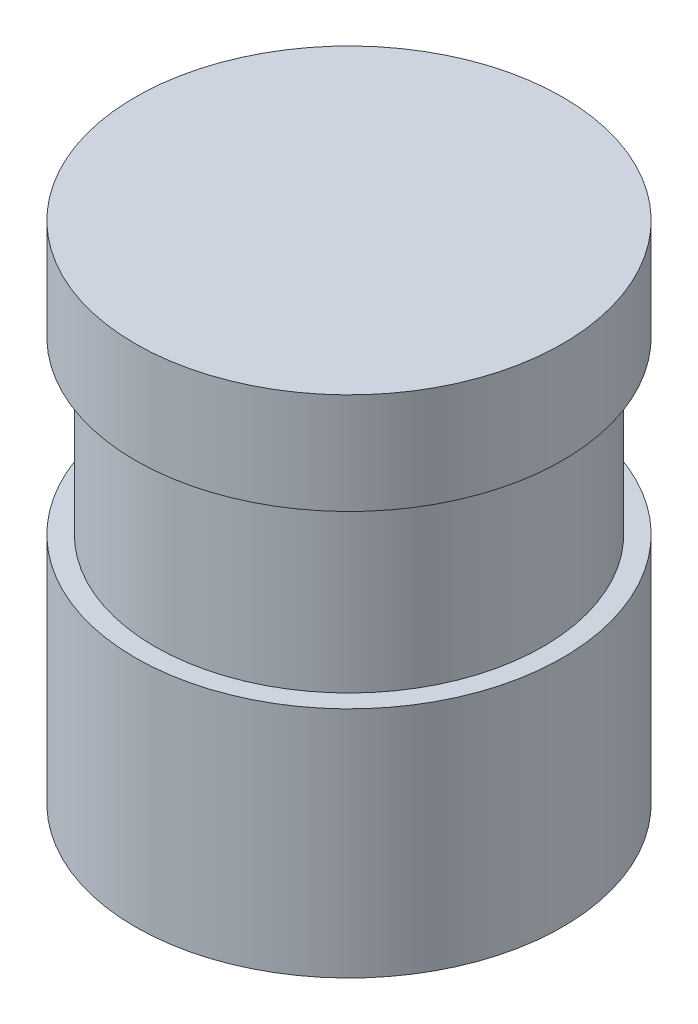
SolidWorks part; units mm, degrees
ref_plane "Спереди" through (0, 0, 0) normal (0, 0, 1) x (1, 0, 0)
ref_plane "Сверху" through (0, 0, 0) normal (0, 1, 0) x (1, 0, 0)
ref_plane "Справа" through (0, 0, 0) normal (1, 0, 0) x (0, 0, -1)
other "Configuration Table"
sketch "Эскиз1" plane through (0, 0, 0) normal (0, 1, 0) x (1, 0, 0)
  circle A0 centre (0, 0) radius 27.5
  dimension "D1" = 55
extrude "Бобышка-Вытянуть1" add sketch "Эскиз1" along normal blind 30
sketch "Эскиз2" plane through (0, 30, 0) normal (0, 1, 0) x (1, 0, 0)
  circle A0 centre (0, 0) radius 25
  dimension "D1" = 50
extrude "Бобышка-Вытянуть2" add sketch "Эскиз2" along normal blind 22
sketch "Эскиз3" plane through (0, 52, 0) normal (0, 1, 0) x (1, 0, 0)
  circle A0 centre (0, 0) radius 27.5 construction
  circle A1 centre (0, 0) radius 27.5
extrude "Бобышка-Вытянуть3" add sketch "Эскиз3" along normal blind 13
